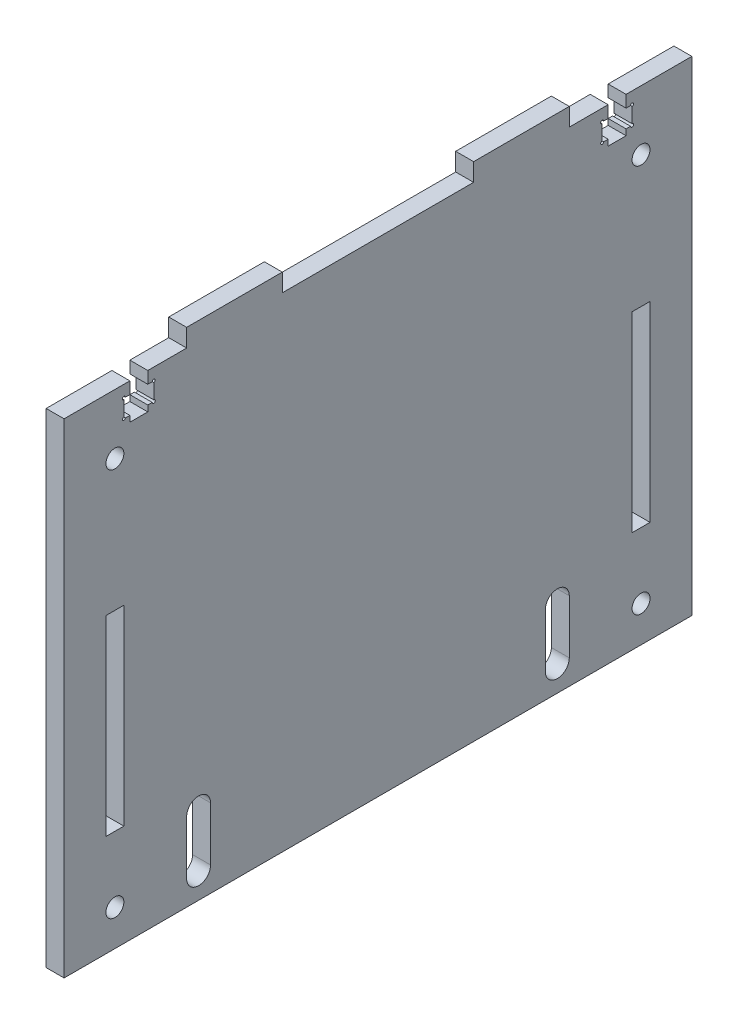
SolidWorks part; units mm, degrees
ref_plane "Front" through (0, 0, 0) normal (0, 0, 1) x (1, 0, 0)
ref_plane "Top" through (0, 0, 0) normal (0, 1, 0) x (1, 0, 0)
ref_plane "Right" through (0, 0, 0) normal (1, 0, 0) x (0, 0, -1)
sketch "Croquis1" plane through (0, 0, 0) normal (1, 0, 0) x (0, 0, -1)
  line L0 (52.5, 85) -> (52.5, 0) construction
  line L1 (0, 0) -> (105, 0)
  line L2 (0, 0) -> (0, 81)
  line L3 (0, 81) -> (20.5, 81)
  line L4 (105, 0) -> (105, 81)
  line L5 (0, 0) -> (105, 81) construction
  line L6 (0, 81) -> (105, 0) construction
  line L7 (68.5, 84) -> (84.5, 81) construction
  line L9 (36.5, 81) -> (36.5, 84)
  line L10 (36.5, 84) -> (20.5, 84)
  line L11 (20.5, 81) -> (20.5, 84)
  line L12 (36.5, 81) -> (20.5, 84) construction
  line L13 (36.5, 84) -> (20.5, 81) construction
  line L14 (68.5, 81) -> (84.5, 84) construction
  line L15 (84.5, 81) -> (84.5, 84)
  line L16 (68.5, 84) -> (84.5, 84)
  line L17 (68.5, 81) -> (68.5, 84)
  line L19 (36.5, 81) -> (68.5, 81)
  line L20 (84.5, 81) -> (105, 81)
  line L21 (98, 17) -> (95, 49) construction
  line L22 (7, 49) -> (10, 49)
  line L23 (7, 49) -> (7, 17)
  line L24 (7, 17) -> (10, 17)
  line L25 (10, 49) -> (10, 17)
  line L26 (7, 49) -> (10, 17) construction
  line L27 (7, 17) -> (10, 49) construction
  line L28 (98, 49) -> (95, 17) construction
  line L29 (95, 49) -> (95, 17)
  line L30 (98, 17) -> (95, 17)
  line L31 (98, 49) -> (98, 17)
  line L32 (98, 49) -> (95, 49)
  line L33 (8.5, 71) -> (8.5, 33) construction
  line L34 (8.5, 33) -> (8.5, 6) construction
  circle A0 centre (8.5, 71) radius 1.5
  circle A1 centre (96.5, 71) radius 1.5
  circle A2 centre (8.5, 6) radius 1.5
  circle A3 centre (96.5, 6) radius 1.5
  point P4 (52.5, 40.5)
  point P12 (28.5, 82.5)
  point P17 (76.5, 82.5)
  point P22 (8.5, 33)
  point P29 (96.5, 33)
  dimension "D10" = 3
  dimension "D13" = 3
  dimension "D15" = 3
  dimension "D1" = 105
  dimension "D2" = 81
  dimension "D3" = 3
  dimension "D4" = 16
  dimension "D5" = 16
  dimension "D6" = 3
  dimension "D7" = 32
  dimension "D8" = 10
  dimension "D9" = 32
  dimension "D11" = 10
  dimension "D12" = 10
  dimension "D14" = 65
extrude "Saliente-Extruir1" add sketch "Croquis1" along normal blind 3
sketch "Croquis2" plane through (3, 0, 0) normal (1, 0, 0) x (0, 0, -1)
  line L0 (14, 81) -> (14, 79)
  line L1 (14, 79) -> (14.75, 79)
  line L2 (15, 78.75) -> (15, 76.25)
  line L3 (14.75, 76) -> (14, 76)
  line L4 (14, 76) -> (14, 75)
  line L5 (14, 75) -> (11, 75)
  line L6 (12.5, 79.0999) -> (12.5, 81) construction
  line L7 (11, 76) -> (11, 75)
  line L8 (10.25, 76) -> (11, 76)
  line L9 (10, 78.75) -> (10, 76.25)
  line L10 (11, 79) -> (10.25, 79)
  line L11 (11, 81) -> (11, 79)
  line L12 (20.5, 81) -> (12.5, 81) construction
  line L14 (52.5, 81) -> (52.5, 61.9658) construction
  line L15 (68.5, 81) -> (36.5, 81) construction
  line L16 (84.5, 81) -> (92.5, 81) construction
  line L17 (92.5, 79.0999) -> (92.5, 81) construction
  line L18 (94, 81) -> (94, 79)
  line L19 (94, 79) -> (94.75, 79)
  line L20 (95, 78.75) -> (95, 76.25)
  line L21 (94.75, 76) -> (94, 76)
  line L22 (94, 76) -> (94, 75)
  line L23 (91, 75) -> (94, 75)
  line L24 (91, 76) -> (91, 75)
  line L25 (90.25, 76) -> (91, 76)
  line L26 (90, 78.75) -> (90, 76.25)
  line L27 (91, 79) -> (90.25, 79)
  line L28 (91, 81) -> (91, 79)
  arc A0 (14.75, 76) -> (15, 76.25) centre (15, 76) ccw
  arc A1 (15, 78.75) -> (14.75, 79) centre (15, 79) ccw
  arc A2 (10, 78.75) -> (10.25, 79) centre (10, 79) cw
  arc A3 (10.25, 76) -> (10, 76.25) centre (10, 76) cw
  arc A4 (94.75, 76) -> (95, 76.25) centre (95, 76) ccw
  arc A5 (95, 78.75) -> (94.75, 79) centre (95, 79) ccw
  arc A6 (90, 78.75) -> (90.25, 79) centre (90, 79) cw
  arc A7 (90.25, 76) -> (90, 76.25) centre (90, 76) cw
  point P3 (12.5, 75)
  point P55 (92.5, 75)
  dimension "D1" = 2
  dimension "D2" = 1.5
  dimension "D3" = 2.5
  dimension "D4" = 3
  dimension "D5" = 1
  dimension "D6" = 8
extrude "Cortar-Extruir1" cut sketch "Croquis2" against normal blind 3
sketch "Croquis3" plane through (3, 0, 0) normal (1, 0, 0) x (0, 0, -1)
  line L0 (52.5, 0) -> (52.5, 87.0941) construction
  line L1 (0, 0) -> (105, 0) construction
  line L2 (22.5, 4.1228) -> (22.5, 13.1228) construction
  line L3 (20.5, 4.1228) -> (20.5, 13.1228)
  line L4 (24.5, 4.1228) -> (24.5, 13.1228)
  line L5 (82.5, 4.1228) -> (82.5, 13.1228) construction
  line L6 (84.5, 4.1228) -> (84.5, 13.1228)
  line L7 (80.5, 4.1228) -> (80.5, 13.1228)
  arc A0 (20.5, 4.1228) -> (24.5, 4.1228) centre (22.5, 4.1228) ccw
  arc A1 (24.5, 13.1228) -> (20.5, 13.1228) centre (22.5, 13.1228) ccw
  arc A2 (84.5, 4.1228) -> (80.5, 4.1228) centre (82.5, 4.1228) cw
  arc A3 (80.5, 13.1228) -> (84.5, 13.1228) centre (82.5, 13.1228) cw
  point P6 (22.5, 8.6228)
  point P11 (20.5, 8.6228)
  point P14 (82.5, 8.6228)
  dimension "D1" = 4
  dimension "D2" = 30
  dimension "D3" = 9
extrude "Cortar-Extruir2" cut sketch "Croquis3" against normal blind 3
